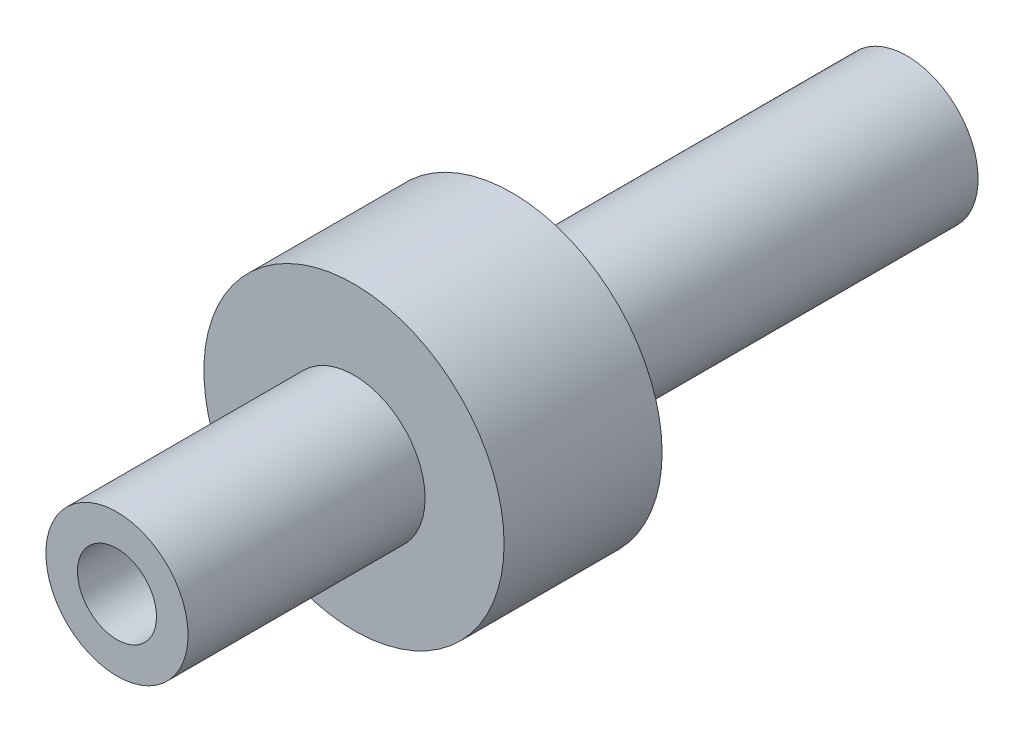
SolidWorks part; units mm, degrees
ref_plane "Front Plane" through (0, 0, 0) normal (0, 0, 1) x (1, 0, 0)
ref_plane "Top Plane" through (0, 0, 0) normal (0, 1, 0) x (1, 0, 0)
ref_plane "Right Plane" through (0, 0, 0) normal (1, 0, 0) x (0, 0, -1)
sketch "Sketch1" plane through (0, 0, 0) normal (0, 0, 1) x (1, 0, 0)
  circle A0 centre (0, 0) radius 4.75
  dimension "D1" = 9.5
extrude "Boss-Extrude1" add sketch "Sketch1" along normal blind 5
sketch "Sketch2" plane through (0, 0, 5) normal (0, 0, 1) x (1, 0, 0)
  circle A0 centre (0, 0) radius 2.25
  dimension "D1" = 4.5
extrude "Boss-Extrude2" add sketch "Sketch2" along normal blind 7.5
sketch "Sketch3" plane through (0, 0, 0) normal (0, 0, -1) x (-1, 0, 0)
  circle A0 centre (0, 0) radius 2.25
  dimension "D1" = 4.5
extrude "Boss-Extrude3" add sketch "Sketch3" along normal blind 12.5
sketch "Sketch4" plane through (0, 0, 12.5) normal (0, 0, 1) x (1, 0, 0)
  circle A0 centre (0, 0) radius 1.25
  dimension "D1" = 2.5
extrude "Cut-Extrude1" cut sketch "Sketch4" against normal blind 5
sketch "Sketch5" plane through (0, 0, -12.5) normal (0, 0, -1) x (-1, 0, 0)
  circle A0 centre (0, 0) radius 1.25
  dimension "D1" = 2.5
extrude "Cut-Extrude2" cut sketch "Sketch5" against normal blind 5
